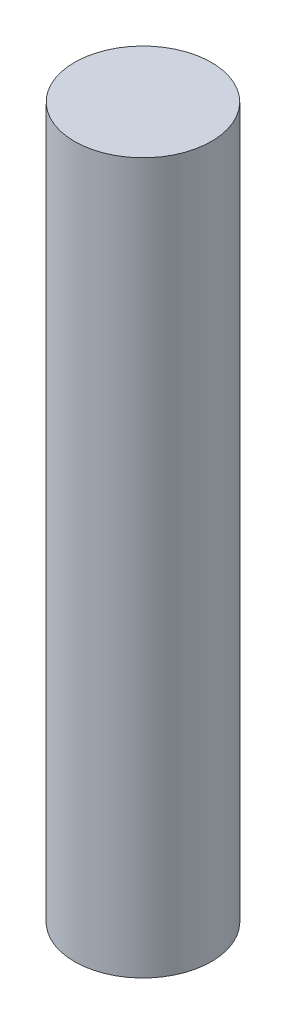
SolidWorks part; units mm, degrees
ref_plane "Front Plane" through (0, 0, 0) normal (0, 0, 1) x (1, 0, 0)
ref_plane "Top Plane" through (0, 0, 0) normal (0, 1, 0) x (1, 0, 0)
ref_plane "Right Plane" through (0, 0, 0) normal (1, 0, 0) x (0, 0, -1)
sketch "Sketch1" plane through (0, 0, 0) normal (0, 1, 0) x (1, 0, 0)
  circle A0 centre (0, 0) radius 5
  dimension "D1" = 10
extrude "Boss-Extrude1" add sketch "Sketch1" along normal blind 51.88
sketch "Sketch2" plane through (0, 51.88, 0) normal (0, 1, 0) x (1, 0, 0)
  point P0 (0, 0)
